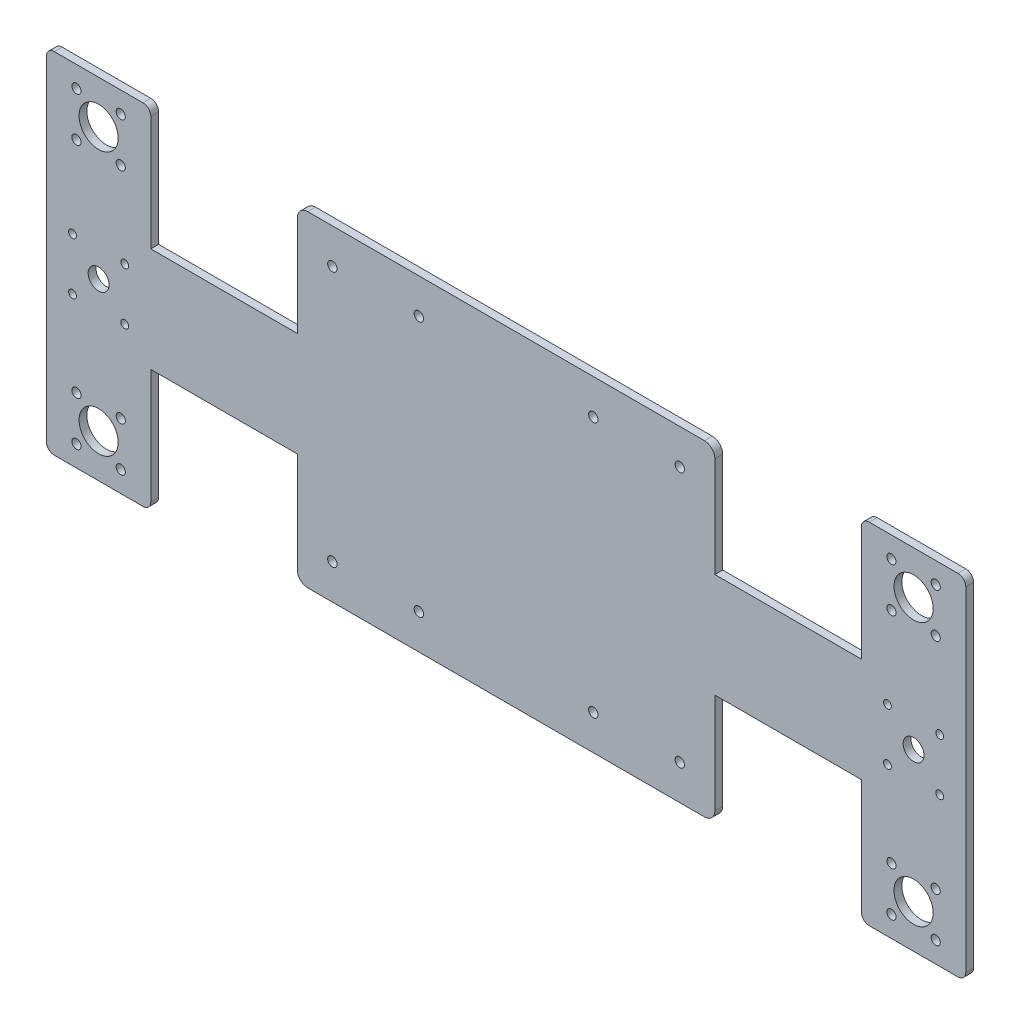
SolidWorks part; units mm, degrees
ref_plane "정면" through (0, 0, 0) normal (0, 0, 1) x (1, 0, 0)
ref_plane "윗면" through (0, 0, 0) normal (0, 1, 0) x (1, 0, 0)
ref_plane "우측면" through (0, 0, 0) normal (1, 0, 0) x (0, 0, -1)
sketch "스케치1" plane through (0, 0, 0) normal (0, 0, 1) x (1, 0, 0)
  line L0 (0, 20) -> (0, -20) construction
  line L1 (-156.15, -20) -> (156.15, -20)
  line L2 (-156.15, -20) -> (-156.15, 20)
  line L3 (-156.15, 20) -> (156.15, 20)
  line L4 (156.15, -20) -> (156.15, 20)
  line L5 (-156.15, -20) -> (156.15, 20) construction
  line L6 (-156.15, 20) -> (156.15, -20) construction
  line L7 (176.15, -20) -> (176.15, 20)
  line L8 (-176.15, -20) -> (-136.15, -20)
  line L9 (-176.15, -20) -> (-176.15, 20)
  line L10 (-176.15, 20) -> (-136.15, 20)
  line L11 (-136.15, -20) -> (-136.15, 20)
  line L12 (-176.15, -20) -> (-136.15, 20) construction
  line L13 (-176.15, 20) -> (-136.15, -20) construction
  line L14 (176.15, -20) -> (136.15, 20) construction
  line L15 (176.15, 20) -> (136.15, -20) construction
  line L16 (176.15, -20) -> (136.15, -20)
  line L17 (136.15, -20) -> (136.15, 20)
  line L18 (176.15, 20) -> (136.15, 20)
  line L19 (146.15, -10) -> (146.15, 10) construction
  line L20 (-166.15, -10) -> (-146.15, -10) construction
  line L21 (-166.15, -10) -> (-166.15, 10) construction
  line L22 (-166.15, 10) -> (-146.15, 10) construction
  line L23 (-146.15, -10) -> (-146.15, 10) construction
  line L24 (-166.15, -10) -> (-146.15, 10) construction
  line L25 (-166.15, 10) -> (-146.15, -10) construction
  line L26 (166.15, -10) -> (146.15, -10) construction
  line L27 (166.15, -10) -> (166.15, 10) construction
  line L28 (166.15, 10) -> (146.15, 10) construction
  circle A0 centre (-156.15, 0) radius 4
  circle A1 centre (156.15, 0) radius 4
  circle A2 centre (-166.15, 10) radius 1.5
  circle A3 centre (-146.15, 10) radius 1.5
  circle A4 centre (-166.15, -10) radius 1.5
  circle A5 centre (-146.15, -10) radius 1.5
  circle A6 centre (146.15, 10) radius 1.5
  circle A7 centre (166.15, 10) radius 1.5
  circle A8 centre (166.15, -10) radius 1.5
  circle A9 centre (146.15, -10) radius 1.5
  point P0 (0, 0)
  point P20 (156.15, 0)
  dimension "D3" = 8
  dimension "D5" = 3
  dimension "D1" = 312.3
  dimension "D4" = 40
  dimension "D6" = 20
extrude "보스-돌출1" add sketch "스케치1" along normal blind 3 contours L4 A1 L16 L7 L18 A7 A8 | L4 A1 L3 L17 L1 A9 A6 | L1 L17 L3 L11 | A0 L2 L10 L9 L8 A4 A2 | A0 L2 L1 L11 L3 A3 A5
fillet "필렛1" radius 7 4 edges at (-176.15, -20, 1.5) (-176.15, 20, 1.5) (176.15, -20, 1.5) (176.15, 20, 1.5)
sketch "스케치2" plane through (0, 0, 3) normal (0, 0, 1) x (1, 0, 0)
  line L0 (0, 49) -> (0, -49) construction
  line L1 (-80, -62.43) -> (80, -62.43)
  line L2 (-80, -62.43) -> (-80, 62.43)
  line L3 (-80, 62.43) -> (80, 62.43)
  line L4 (80, -62.43) -> (80, 62.43)
  line L5 (-80, -62.43) -> (80, 62.43) construction
  line L6 (-80, 62.43) -> (80, -62.43) construction
  line L7 (-66.575, -49) -> (66.575, -49)
  line L8 (-66.575, -49) -> (-66.575, 49)
  line L9 (-66.575, 49) -> (66.575, 49)
  line L10 (66.575, -49) -> (66.575, 49)
  line L11 (-66.575, -49) -> (66.575, 49) construction
  line L12 (-66.575, 49) -> (66.575, -49) construction
  line L13 (-33.425, -49) -> (33.425, -49)
  line L14 (-33.425, -49) -> (-33.425, 49)
  line L15 (-33.425, 49) -> (33.425, 49)
  line L16 (33.425, -49) -> (33.425, 49)
  line L17 (-33.425, -49) -> (33.425, 49) construction
  line L18 (-33.425, 49) -> (33.425, -49) construction
  circle A0 centre (-66.575, 49) radius 1.8
  circle A1 centre (-33.425, 49) radius 1.8
  circle A2 centre (-66.575, -49) radius 1.8
  circle A3 centre (-33.425, -49) radius 1.8
  circle A4 centre (33.425, -49) radius 1.8
  circle A5 centre (66.575, -49) radius 1.8
  circle A6 centre (66.575, 49) radius 1.8
  circle A7 centre (33.425, 49) radius 1.8
  point P0 (0, 0)
  point P6 (0, 0)
  point P11 (0, 0)
  line M9 (-169.15, -20) -> (169.15, -20)
  line M13 (169.15, 20) -> (-169.15, 20)
  dimension "D5" = 3.6
  dimension "D1" = 160
  dimension "D2" = 98
  dimension "D3" = 66.85
  dimension "D4" = 33.15
  dimension "D6" = 13.43
extrude "보스-돌출2" add sketch "스케치2" against normal blind 3 contours L15 A7 L9 A6 L10 L4 L3 L2 L8 A0 A1 M13 | L8 L2 M9 M13 | L10 A5 L7 A4 L13 A3 A2 L8 L2 L1 L4 M9 | L14 L8 M9 M13 | A1 L9 A0 L8 L14 M13 | L16 A7 L15 A1 L14 M13 | L16 L14 M9 M13 | L16 L10 M9 M13 | L9 A7 L16 L10 A6 M13 | L7 A5 L10 L16 A4 M9 | A3 L14 L8 A2 L7 M9 | L13 A4 L16 L14 A3 M9
fillet "필렛2" radius 4 4 edges at (-80, -62.43, 1.5) (80, -62.43, 1.5) (80, 62.43, 1.5) (-80, 62.43, 1.5)
sketch "스케치3" plane through (0, 0, 3) normal (0, 0, 1) x (1, 0, 0)
  line L0 (-176.15, -13) -> (-176.15, 13) construction
  line L1 (-176.15, -66.9706) -> (-136.15, -66.9706)
  line L2 (-176.15, -66.9706) -> (-176.15, 66.9706)
  line L3 (-176.15, 66.9706) -> (-136.15, 66.9706)
  line L4 (-136.15, -66.9706) -> (-136.15, 66.9706)
  line L5 (-176.15, -66.9706) -> (-136.15, 66.9706) construction
  line L6 (-176.15, 66.9706) -> (-136.15, -66.9706) construction
  line L7 (-176.15, 0) -> (-136.15, 0) construction
  line L8 (-164.6353, -42) -> (-164.6353, -58.9706)
  line L9 (-164.6353, 42) -> (-147.6647, 42) construction
  line L10 (-164.6353, 42) -> (-164.6353, 58.9706) construction
  line L11 (-164.6353, 58.9706) -> (-147.6647, 58.9706) construction
  line L12 (-147.6647, 42) -> (-147.6647, 58.9706) construction
  line L13 (-164.6353, 42) -> (-147.6647, 58.9706) construction
  line L14 (-164.6353, 58.9706) -> (-147.6647, 42) construction
  line L15 (-164.6353, -42) -> (-147.6647, -58.9706) construction
  line L16 (-164.6353, -58.9706) -> (-147.6647, -42) construction
  line L17 (-164.6353, -42) -> (-147.6647, -42)
  line L18 (-147.6647, -42) -> (-147.6647, -58.9706)
  line L19 (-164.6353, -58.9706) -> (-147.6647, -58.9706)
  line L20 (-156.15, 66.9706) -> (-156.15, -66.9706) construction
  line L21 (-80, 20) -> (-169.15, 20) construction
  circle A0 centre (-156.15, 0) radius 4
  circle A1 centre (-164.6353, 58.9706) radius 1.75
  circle A2 centre (-164.6353, -58.9706) radius 1.75
  circle A3 centre (-147.6647, 58.9706) radius 1.75
  circle A4 centre (-147.6647, -58.9706) radius 1.75
  circle A5 centre (-164.6353, 42) radius 1.75
  circle A6 centre (-164.6353, -42) radius 1.75
  circle A7 centre (-147.6647, 42) radius 1.75
  circle A8 centre (-147.6647, -42) radius 1.75
  circle A9 centre (-156.15, 50.4853) radius 7.5
  circle A10 centre (-156.15, -50.4853) radius 7.5
  circle A11 centre (-156.15, 50.4853) radius 12 construction
  point P11 (-156.15, 50.4853)
  point P20 (-156.15, -50.4853)
  line M24 (-80, 20) -> (-169.15, 20)
  arc M25 (-169.15, 20) -> (-176.15, 13) centre (-169.15, 13) ccw
  arc M27 (-176.15, -13) -> (-169.15, -20) centre (-169.15, -13) ccw
  line M28 (-169.15, -20) -> (-80, -20)
  dimension "D2" = 3.5
  dimension "D3" = 15
  dimension "D1" = 24
  dimension "D4" = 8
  dimension "D5" = 22
extrude "보스-돌출3" add sketch "스케치3" against normal blind 3 contours L4 L3 L2 A9 A7 A5 A3 A1 M24 M25 | L1 L4 L2 L17 A8 L18 A4 L19 A2 L8 A6 M28 M27 | L18 A8 L17 A6 L8 A2 L19 A4 A10
fillet "필렛3" radius 3 4 edges at (-176.15, 66.9706, 1.5) (-136.15, 66.9706, 1.5) (-176.15, -66.9706, 1.5) (-136.15, -66.9706, 1.5)
mirror "대칭 복사1" about plane through (0, 0, 0) normal (1, 0, 0) of "보스-돌출3"
fillet "필렛5" radius 3 4 edges at (136.15, -66.9706, 1.5) (136.15, 66.9706, 1.5) (176.15, 66.9706, 1.5) (176.15, -66.9706, 1.5)
